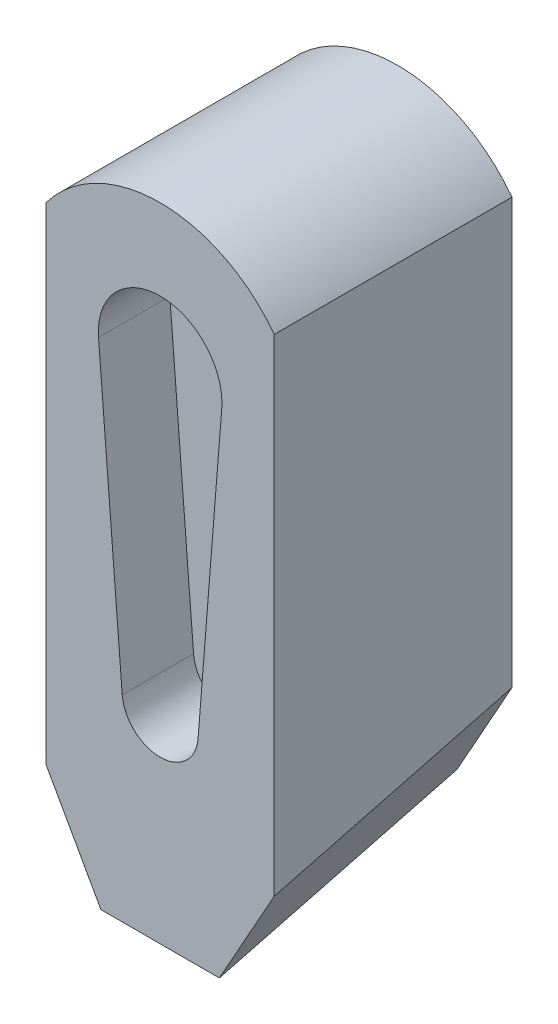
SolidWorks part; units mm, degrees
material "ABS"
ref_plane "Front Plane" through (0, 0, 0) normal (0, 0, 1) x (1, 0, 0)
ref_plane "Top Plane" through (0, 0, 0) normal (0, 1, 0) x (1, 0, 0)
ref_plane "Right Plane" through (0, 0, 0) normal (1, 0, 0) x (0, 0, -1)
sketch "Sketch1" plane through (0, 0, 0) normal (0, 0, 1) x (1, 0, 0)
  line L0 (-6.096, 4.572) -> (-6.096, -33.528)
  line L1 (-6.096, -33.528) -> (6.096, -33.528)
  line L2 (6.096, -33.528) -> (6.096, 4.572)
  arc A0 (-6.096, 4.572) -> (6.096, 4.572) centre (0, 0) cw
  point P7 (0, -33.528)
  dimension "D1" = 7.62
  dimension "D3" = 38.1
  dimension "D2" = 12.192
extrude "Boss-Extrude1" add sketch "Sketch1" along normal blind 12.7
sketch "Sketch2" plane through (0, 0, 12.7) normal (0, 0, 1) x (1, 0, 0)
  line L0 (3.2916, -0.2621) -> (2.0256, -16.1633)
  line L1 (-2.0256, -16.1633) -> (-3.2916, -0.2621)
  arc A0 (3.2916, -0.2621) -> (-3.2916, -0.2621) centre (0, 0) ccw
  arc A1 (2.0256, -16.1633) -> (-2.0256, -16.1633) centre (0, -16.002) cw
  dimension "D1" = 3.302
  dimension "D2" = 2.032
  dimension "D3" = 16.002
extrude "Cut-Extrude1" cut sketch "Sketch2" against normal blind 3.81 and the other way through all
sketch "Sketch3" plane through (6.096, 0, 0) normal (1, 0, 0) x (0, 0, -1)
  line L0 (-12.7, -33.528) -> (-12.7, 4.572) construction
  line L1 (-12.7, -33.528) -> (-12.7, -26.67)
  line L2 (-12.7, -26.67) -> (0, -23.368)
  line L3 (0, -33.528) -> (0, 4.572) construction
  line L4 (0, -23.368) -> (0, -33.528)
  line L5 (0, -33.528) -> (-12.7, -33.528)
  dimension "D1" = 6.858
  dimension "D2" = 10.16
extrude "Cut-Extrude2" cut sketch "Sketch3" against normal through all
sketch "Sketch4" plane through (0, 0, 8.89) normal (0, 0, 1) x (1, 0, 0)
  circle A0 centre (0, 0) radius 1.5875
  dimension "D1" = 3.175
extrude "Cut-Extrude3" cut sketch "Sketch4" against normal through all
sketch "Sketch5" plane through (0, 0, 0) normal (0, 0, -1) x (-1, 0, 0)
  circle A0 centre (0, 0) radius 3.175
  dimension "D1" = 6.35
extrude "Cut-Extrude4" cut sketch "Sketch5" against normal blind 6.35
chamfer "Chamfer1" distance 1.016 angle 45 1 edges at (-3.175, 0, 6.35)
chamfer "Chamfer2" distance 5.08 angle 30 2 edges at (-6.096, -25.019, 6.35) (6.096, -25.019, 6.35)
